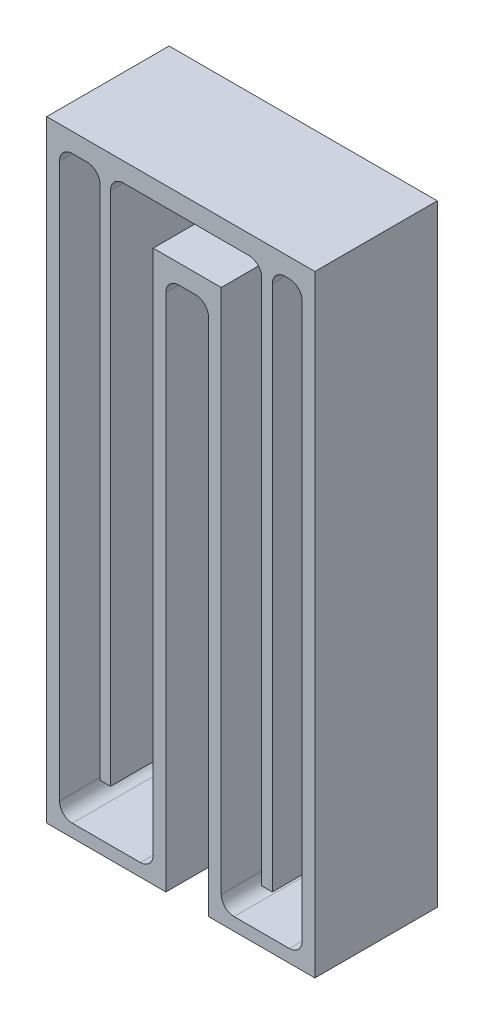
SolidWorks part; units mm, degrees
ref_plane "Front Plane" through (0, 0, 0) normal (0, 0, 1) x (1, 0, 0)
ref_plane "Top Plane" through (0, 0, 0) normal (0, 1, 0) x (1, 0, 0)
ref_plane "Right Plane" through (0, 0, 0) normal (1, 0, 0) x (0, 0, -1)
sketch "Sketch1" plane through (0, 0, 0) normal (0, 0, 1) x (1, 0, 0)
  line L0 (0, 0) -> (0, 97.6)
  line L1 (2.4, 100) -> (5.6, 100)
  line L2 (8, 97.6) -> (8, 0)
  line L3 (-10, 115) -> (18, 115)
  line L4 (18, 109) -> (18, 10)
  line L5 (-10.4, 109) -> (-10.4, 12)
  line L6 (8, 0) -> (28, 0)
  line L7 (28, 0) -> (28, 115)
  line L8 (0, 0) -> (-22.4, 0)
  line L9 (-22.4, 0) -> (-22.4, 115)
  line L10 (18, 115) -> (28, 115)
  line L11 (-22.4, 115) -> (-10, 115)
  line L12 (-2.4, 103.6) -> (10.4, 103.6)
  line L13 (10.4, 103.6) -> (10.4, 4.8)
  line L14 (12.8, 2.4) -> (23.2, 2.4)
  line L15 (25.6, 4.8) -> (25.6, 109)
  line L16 (-2.4, 103.6) -> (-2.4, 4.8)
  line L17 (-4.8, 2.4) -> (-17.6, 2.4)
  line L18 (-20, 4.8) -> (-20, 109)
  line L19 (-17.6, 111.4) -> (-14.8, 111.4)
  line L20 (-12.4, 109) -> (-12.4, 12)
  line L21 (-12.4, 12) -> (-10.4, 12)
  line L22 (-8, 111.4) -> (15.6, 111.4)
  line L23 (18, 10) -> (20, 10)
  line L24 (20, 10) -> (20, 109)
  line L25 (22.4, 111.4) -> (23.2, 111.4)
  arc A0 (5.6, 100) -> (8, 97.6) centre (5.6, 97.6) cw
  arc A1 (0, 97.6) -> (2.4, 100) centre (2.4, 97.6) cw
  arc A2 (-8, 111.4) -> (-10.4, 109) centre (-8, 109) ccw
  arc A3 (15.6, 111.4) -> (18, 109) centre (15.6, 109) cw
  arc A4 (23.2, 111.4) -> (25.6, 109) centre (23.2, 109) cw
  arc A5 (20, 109) -> (22.4, 111.4) centre (22.4, 109) cw
  arc A6 (-14.8, 111.4) -> (-12.4, 109) centre (-14.8, 109) cw
  arc A7 (-20, 109) -> (-17.6, 111.4) centre (-17.6, 109) cw
  arc A8 (23.2, 2.4) -> (25.6, 4.8) centre (23.2, 4.8) ccw
  arc A9 (10.4, 4.8) -> (12.8, 2.4) centre (12.8, 4.8) ccw
  arc A10 (-17.6, 2.4) -> (-20, 4.8) centre (-17.6, 4.8) cw
  arc A11 (-2.4, 4.8) -> (-4.8, 2.4) centre (-4.8, 4.8) cw
  point P8 (4, 115)
  point P11 (4, 100)
  point P17 (0, 0)
  point P27 (27.8739, 108.3109)
  point P31 (0, 0)
  point P32 (0, 0)
  point P33 (0, 0)
  point P34 (0, 0)
  point P35 (-10, 107.6)
  point P36 (-6.0174, 110)
  point P37 (-8, 110)
  point P38 (11.533, 110)
  point P39 (16, 110)
  point P40 (0, 0)
  point P41 (0, 0)
  point P44 (8, 100)
  point P47 (0, 100)
  point P52 (18, 111.4)
  point P59 (-12.4, 111.4)
  dimension "D20" = 2.4
  dimension "D1" = 8
  dimension "D2" = 100
  dimension "D3" = 10
  dimension "D4" = 15
  dimension "D5" = 10
  dimension "D6" = 10
  dimension "D7" = 12
  dimension "D8" = 2.4
  dimension "D9" = 10
  dimension "D10" = 2.4
  dimension "D11" = 3.6
  dimension "D12" = 2
  dimension "D13" = 2
  dimension "D14" = 3.6
  dimension "D15" = 2.4
  dimension "D16" = 2.4
  dimension "D17" = 2.4
  dimension "D18" = 2.4
  dimension "D19" = 10
extrude "Boss-Extrude1" add sketch "Sketch1" along normal blind 20
sketch "Sketch2" plane through (0, 0, 0) normal (0, 0, 1) x (1, 0, 0)
  line L0 (28, 115) -> (-22.4, 115) construction
  line L1 (-22.4, 115) -> (-22.4, 0) construction
  line L2 (-22.4, 0) -> (0, 0) construction
  line L3 (0, 0) -> (0, 97.6) construction
  line L4 (2.4, 100) -> (5.6, 100) construction
  line L5 (8, 97.6) -> (8, 0) construction
  line L6 (8, 0) -> (28, 0) construction
  line L7 (28, 0) -> (28, 115) construction
  line L8 (28, 115) -> (-22.4, 115)
  line L9 (-22.4, 115) -> (-22.4, 0)
  line L10 (-22.4, 0) -> (0, 0)
  line L11 (0, 0) -> (0, 97.6)
  line L12 (2.4, 100) -> (5.6, 100)
  line L13 (8, 97.6) -> (8, 0)
  line L14 (8, 0) -> (28, 0)
  line L15 (28, 0) -> (28, 115)
  arc A0 (2.4, 100) -> (0, 97.6) centre (2.4, 97.6) ccw construction
  arc A1 (8, 97.6) -> (5.6, 100) centre (5.6, 97.6) ccw construction
  arc A2 (2.4, 100) -> (0, 97.6) centre (2.4, 97.6) ccw
  arc A3 (8, 97.6) -> (5.6, 100) centre (5.6, 97.6) ccw
extrude "Boss-Extrude2" add sketch "Sketch2" against normal blind 3
sketch "Sketch5" plane through (28, 0, 0) normal (1, 0, 0) x (0, 0, -1)
  line L1 (-16.5057, 72.6906) -> (-14.5057, 72.6906)
  line L2 (-16.5057, 72.6906) -> (-16.5057, 57.6906)
  line L3 (-16.5057, 57.6906) -> (-14.5057, 57.6906)
  line L4 (-14.5057, 72.6906) -> (-14.5057, 57.6906)
  dimension "D1" = 2
  dimension "D2" = 15
